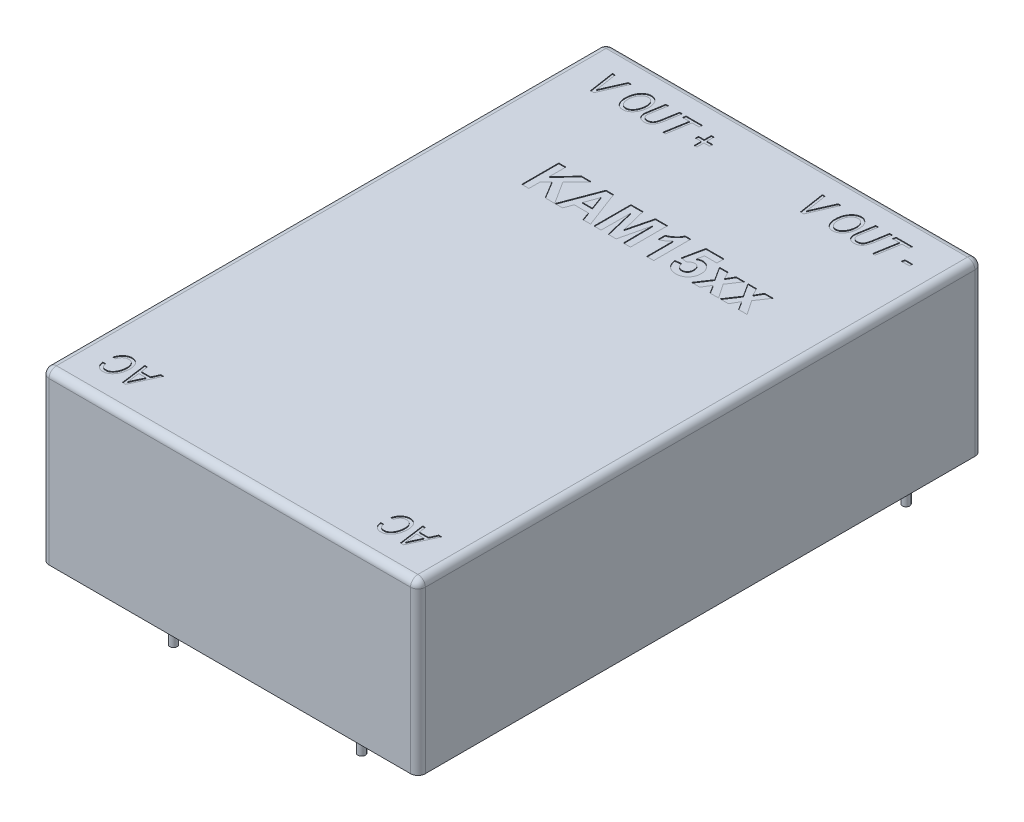
SolidWorks part; units mm, degrees
ref_plane "Спереди" through (0, 0, 0) normal (0, 0, 1) x (1, 0, 0)
ref_plane "Сверху" through (0, 0, 0) normal (0, 1, 0) x (1, 0, 0)
ref_plane "Справа" through (0, 0, 0) normal (1, 0, 0) x (0, 0, -1)
sketch "Эскиз1" plane through (0, 0, 0) normal (0, 1, 0) x (1, 0, 0)
  line L1 (-25.4, -38.1) -> (25.4, -38.1)
  line L2 (-25.4, -38.1) -> (-25.4, 38.1)
  line L3 (-25.4, 38.1) -> (25.4, 38.1)
  line L4 (25.4, -38.1) -> (25.4, 38.1)
  line L5 (-25.4, -38.1) -> (25.4, 38.1) construction
  line L6 (-25.4, 38.1) -> (25.4, -38.1) construction
  point P0 (0, 0)
extrude "Бобышка-Вытянуть1" add sketch "Эскиз1" along normal blind 22.8
fillet "Скругление1" radius 1 8 edges at (25.4, 22.8, 0) (0, 22.8, -38.1) (0, 22.8, 38.1) (25.4, 11.4, 38.1) (-25.4, 11.4, 38.1) (-25.4, 11.4, -38.1) (25.4, 11.4, -38.1) (-25.4, 22.8, 0)
sketch "Эскиз2" plane through (0, 0, 0) normal (0, -1, 0) x (1, 0, 0)
  line L0 (0, 35.9711) -> (0, -43.334) construction
  line L1 (-24.4, 38.1) -> (24.4, 38.1) construction
  line L2 (-69.0993, -32.9) -> (35.1092, -32.9) construction
  line L4 (43.6927, 33) -> (-31.2557, 33) construction
  circle A0 centre (-12.7, 33) radius 0.5
  circle A1 centre (12.7, 33) radius 0.5
  circle A2 centre (-20.3, -32.9) radius 0.5
  circle A3 centre (20.3, -32.9) radius 0.5
  circle A4 centre (12.7, -22.9) radius 0.5
  point P17 (0, 0)
  point P18 (0, 0)
  point P21 (0, 0)
  dimension "D1" = 25.4
  dimension "D2" = 40.6
  dimension "D3" = 5.1
  dimension "D4" = 55.9
  dimension "D5" = 10
extrude "Бобышка-Вытянуть2" add sketch "Эскиз2" along normal blind 6
sketch "Эскиз4" plane through (0, 22.8, 0) normal (0, 1, 0) x (1, 0, 0)
  line L0 (-21.5586, 31.1) -> (21.5586, 31.1) construction
  line L1 (0, 37.1) -> (0, 0) construction
  line L2 (24.4, 37.1) -> (-24.4, 37.1) construction
  line L3 (-21.5586, -31.1) -> (21.5586, -31.1) construction
  line L4 (0, 0) -> (-19.8175, 0) construction
  line L5 (-21.5586, 15.5136) -> (21.5586, 15.5136) construction
  text T0 "V OUT +"
  text T1 "V OUT -"
  text T2 "AC"
  text T3 "AC"
  text T4 "<b>KAM15xx</b>" font "Arial" height 5
  dimension "D1" = 6
extrude "Вырез-Вытянуть1" cut sketch "Эскиз4" against normal blind 0.1
